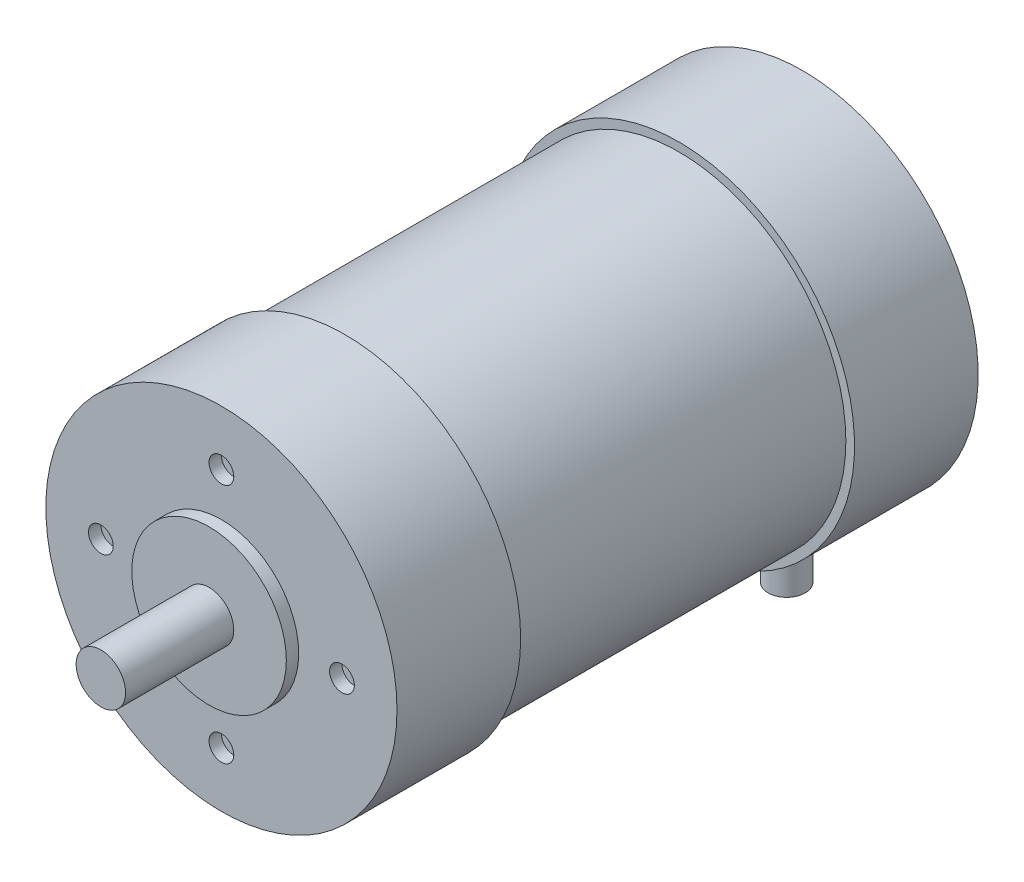
SolidWorks part; units mm, degrees
material "2024 合金"
ref_plane "前视基准面" through (0, 0, 0) normal (0, 0, 1) x (1, 0, 0)
ref_plane "上视基准面" through (0, 0, 0) normal (0, 1, 0) x (1, 0, 0)
ref_plane "右视基准面" through (0, 0, 0) normal (1, 0, 0) x (0, 0, -1)
other "Configuration Table"
sketch "草图1" plane through (0, 0, 0) normal (0, 0, 1) x (1, 0, 0)
  circle A0 centre (0, 0) radius 27
extrude "凸台-拉伸1" add sketch "草图1" against normal blind 94
sketch "草图2" plane through (0, 0, 0) normal (0, 0, 1) x (1, 0, 0)
  circle A0 centre (0, 0) radius 28.4
  circle A1 centre (0, 0) radius 27
extrude "凸台-拉伸2" add sketch "草图2" against normal blind 20
sketch "草图3" plane through (0, 0, -94) normal (0, 0, -1) x (-1, 0, 0)
  circle A0 centre (0, 0) radius 27
  circle A1 centre (0, 0) radius 28.4
extrude "凸台-拉伸3" add sketch "草图3" against normal blind 20
ref_plane "基准面1" through (0, -20, 0) normal (0, 1, 0) x (1, 0, 0)
sketch "草图5" plane through (0, -20, 0) normal (0, 1, 0) x (1, 0, 0)
  line L0 (0, 94) -> (0, 74.863)
  line L1 (28.4, 94) -> (-28.4, 94) construction
  line L2 (0, 84.4315) -> (-7, 84.4315)
  line L3 (0, 84.4315) -> (7, 84.4315)
  circle A0 centre (-7, 84.4315) radius 3
  circle A1 centre (7, 84.4315) radius 3
  dimension "D1" = 7
  dimension "D2" = 7
extrude "凸台-拉伸4" add sketch "草图5" against normal blind 15
sketch "草图9" plane through (0, 0, 0) normal (0, 0, 1) x (1, 0, 0)
  circle A0 centre (0, 0) radius 4
extrude "凸台-拉伸6" add sketch "草图9" along normal blind 19.5
sketch "草图10" plane through (0, 0, 0) normal (0, 0, 1) x (1, 0, 0)
  circle A0 centre (0, 0) radius 4
  circle A1 centre (0, 0) radius 12.5
extrude "凸台-拉伸7" add sketch "草图10" along normal blind 2
sketch "草图11" plane through (0, 0, 0) normal (0, 0, 1) x (1, 0, 0)
  line L0 (0, 0) -> (19.5, 0)
  line L1 (0, 0) -> (0, -19.5)
  line L2 (0, 0) -> (-19.5, 0)
  line L3 (0, 0) -> (0, 19.5)
  circle A0 centre (0, 0) radius 19.5
  circle A1 centre (19.5, 0) radius 2
  circle A2 centre (0, 19.5) radius 2
  circle A3 centre (-19.5, 0) radius 2
  circle A4 centre (0, -19.5) radius 2
extrude "切除-拉伸2" cut sketch "草图11" against normal blind 2 contours A0 A4 | A0 A4 L1 | L1 A4 A0 | A0 A3 L2 | L2 A3 A0 | A0 A3 | A0 A1 | L0 A1 A0 | A0 A1 L0 | L3 A2 A0 | A0 A2 L3 | A0 A2
